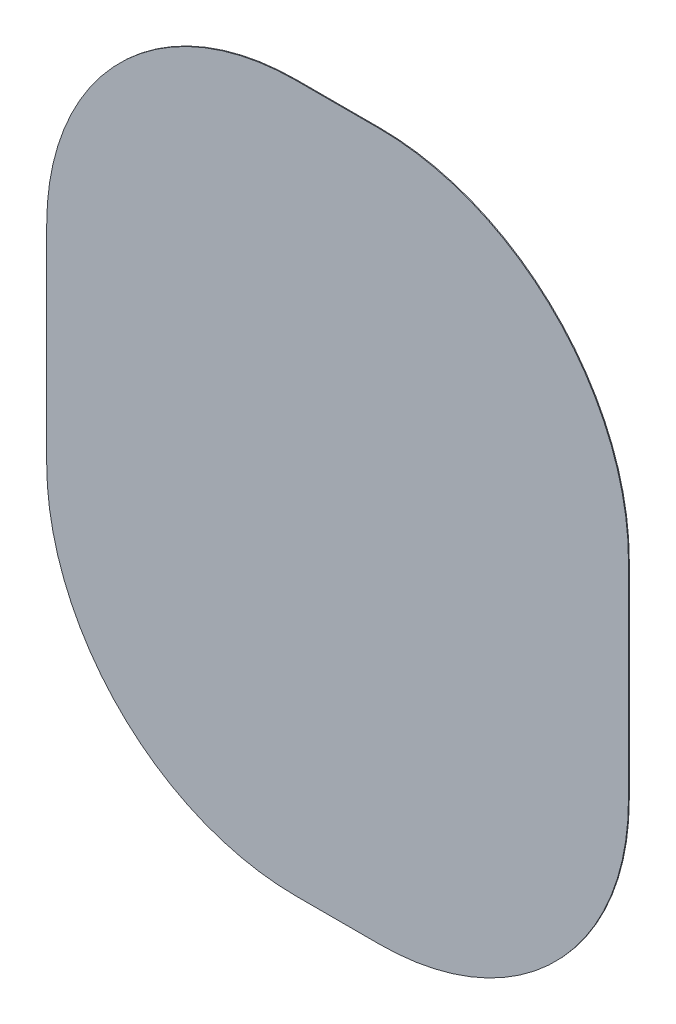
SolidWorks part; units mm, degrees
ref_plane "Front Plane" through (0, 0, 0) normal (0, 0, 1) x (1, 0, 0)
ref_plane "Top Plane" through (0, 0, 0) normal (0, 1, 0) x (1, 0, 0)
ref_plane "Right Plane" through (0, 0, 0) normal (1, 0, 0) x (0, 0, -1)
sketch "Sketch1" plane through (0, 0, 0) normal (0, 0, 1) x (1, 0, 0)
  line L1 (5, -42.5) -> (-5, -42.5)
  line L2 (35, -12.5) -> (35, 12.5)
  line L3 (5, 42.5) -> (-5, 42.5)
  line L4 (-35, -12.5) -> (-35, 12.5)
  line L5 (35, -42.5) -> (-35, 42.5) construction
  line L6 (35, 42.5) -> (-35, -42.5) construction
  arc A0 (-5, -42.5) -> (-35, -12.5) centre (-5, -12.5) cw
  arc A1 (5, -42.5) -> (35, -12.5) centre (5, -12.5) ccw
  arc A2 (35, 12.5) -> (5, 42.5) centre (5, 12.5) ccw
  arc A3 (-5, 42.5) -> (-35, 12.5) centre (-5, 12.5) ccw
  point P0 (0, 0)
  dimension "D3" = 30
  dimension "D1" = 85
  dimension "D2" = 70
extrude "Boss-Extrude1" add sketch "Sketch1" along normal blind 0.1
